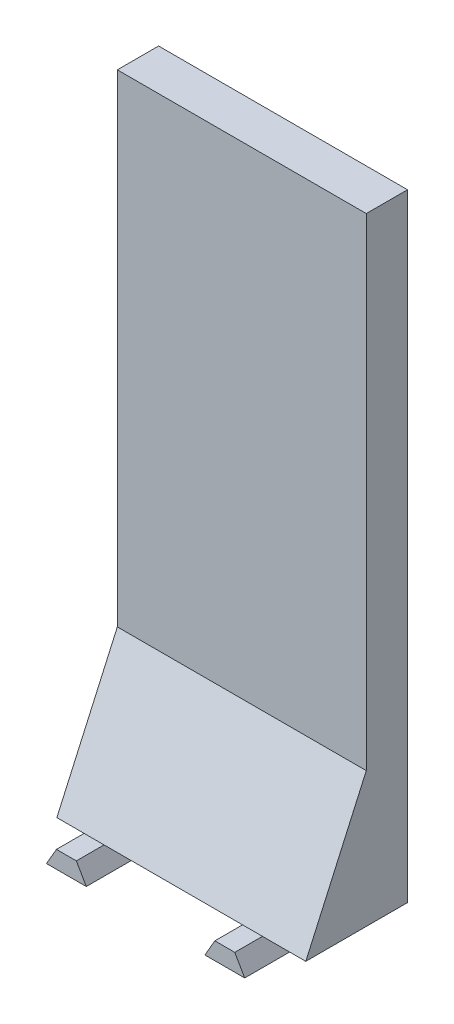
SolidWorks part; units mm, degrees
ref_plane "Front Plane" through (0, 0, 0) normal (0, 0, 1) x (1, 0, 0)
ref_plane "Top Plane" through (0, 0, 0) normal (0, 1, 0) x (1, 0, 0)
ref_plane "Right Plane" through (0, 0, 0) normal (1, 0, 0) x (0, 0, -1)
sketch "Sketch1" plane through (0, 0, 0) normal (0, 0, 1) x (1, 0, 0)
  line L1 (676.5562, 897.8708) -> (701.5562, 897.8708)
  line L2 (676.5562, 897.8708) -> (676.5562, 899.8708)
  line L3 (676.5562, 899.8708) -> (701.5562, 899.8708)
  line L4 (701.5562, 897.8708) -> (701.5562, 899.8708)
  dimension "D1" = 2
extrude "Boss-Extrude1" add sketch "Sketch1" along normal blind 20
sketch "Sketch2" plane through (0, 0, 20) normal (0, 0, 1) x (1, 0, 0)
  line L1 (676.5562, 897.8708) -> (701.5562, 897.8708) construction
  line L7 (679.2969, 897.8708) -> (678.2969, 896.1387)
  line L8 (678.2969, 896.1387) -> (682.2969, 896.1387)
  line L9 (682.2969, 896.1387) -> (681.2969, 897.8708)
  line L11 (697.2056, 897.8708) -> (695.2056, 897.8708)
  line L12 (681.2969, 897.8708) -> (679.2969, 897.8708)
  line L14 (695.2056, 897.8708) -> (694.2056, 896.1387)
  line L17 (694.2056, 896.1387) -> (698.2056, 896.1387)
  line L18 (698.2056, 896.1387) -> (697.2056, 897.8708)
  dimension "D1" = 2
  dimension "D2" = 2
  dimension "D3" = 60
  dimension "D4" = 60
  dimension "D5" = 60
  dimension "D6" = 60
  dimension "D7" = 2
  dimension "D8" = 2
extrude "Boss-Extrude2" add sketch "Sketch2" against normal blind 15 separate body
sketch "Sketch4" plane through (0, 899.8708, 0) normal (0, 1, 0) x (1, 0, 0)
  line L0 (676.5562, -7) -> (701.5562, -7)
  line L1 (676.5562, -7) -> (676.5562, -20)
  line L2 (676.5562, -20) -> (676.5562, 0) construction
  line L3 (676.5562, -20) -> (701.5562, -20)
  line L4 (701.5562, -20) -> (701.5562, 0) construction
  line L9 (701.5562, -7) -> (701.5562, -20)
  dimension "D1" = 13
extrude "Boss-Extrude3" add sketch "Sketch4" along normal blind 60
sketch "Sketch5" plane through (676.5562, 0, 0) normal (-1, 0, 0) x (0, 0, 1)
  line L0 (11.1431, 959.8708) -> (20, 959.8708)
  line L2 (20, 959.8708) -> (20, 897.8708)
  line L3 (20, 897.8708) -> (0, 897.8708) construction
  line L5 (17.2174, 897.8708) -> (11.1431, 911.421)
  line L6 (11.1431, 911.421) -> (11.1431, 959.8708)
  line L7 (7, 959.8708) -> (20, 959.8708) construction
  line L8 (20, 959.8708) -> (20, 897.8708) construction
  line L9 (20, 897.8708) -> (17.2174, 897.8708)
extrude "Cut-Extrude1" cut sketch "Sketch5" against normal blind 25
sketch "Sketch6" plane through (676.5562, 0, 0) normal (-1, 0, 0) x (0, 0, 1)
  line L1 (0, 899.8708) -> (7, 899.8708)
  line L2 (0, 899.8708) -> (0, 897.8615)
  line L3 (7, 899.8708) -> (7, 897.8615)
  line L4 (0, 897.8615) -> (7, 897.8615)
extrude "Cut-Extrude3" cut sketch "Sketch6" against normal blind 25
sketch "Sketch8" plane through (0, 0, 7) normal (0, 0, -1) x (-1, 0, 0)
  line L0 (-676.5562, 959.8708) -> (-676.5562, 897.8708) construction
  line L1 (-691.5562, 899.7696) -> (-686.5562, 899.7696)
  line L2 (-701.5562, 959.8708) -> (-701.5562, 897.8708) construction
  line L3 (-686.5562, 899.7696) -> (-686.5562, 903.7696)
  line L4 (-686.5562, 903.7696) -> (-691.5562, 903.7696)
  line L5 (-691.5562, 903.7696) -> (-691.5562, 899.7696)
  point P6 (-689.0562, 899.7696)
  dimension "D1" = 10
  dimension "D2" = 10
  dimension "D3" = 4
extrude "Boss-Extrude5" add sketch "Sketch8" along normal blind 6
hole_wizard "Ø2.5 (2.5) Diameter Hole1" positions "Sketch10" profile "Sketch11" hole size "Ø2.5" standard "ANSI Metric" end condition through all
sketch "Sketch10" plane through (0, 903.7696, 0) normal (0, 1, 0) x (1, 0, 0)
  line L0 (686.5562, -7) -> (691.5562, -7) construction
  line L1 (686.5562, -1) -> (686.5562, -7) construction
  point P0 (689.0562, -3.5)
  point P9 (687.1584, -1.9814)
  dimension "D1" = 3.5
  dimension "D2" = 2.5
sketch "Sketch11" plane through (689.0562, 903.7696, 3.5) normal (1, 0, 0) x (0, 0, 1)
  line L0 (0, 0) -> (0, 7.6309)
  line L1 (0, 7.6309) -> (1.25, 7.6309)
  line L2 (1.25, 7.6309) -> (1.25, 0)
  line L5 (1.25, 0) -> (0, 0)
  line L11 (0, -6.35) -> (0, 107.95) construction
  dimension "Thru Hole Dia." = 2.5
  dimension "Thru Hole Depth" = 7.6309
